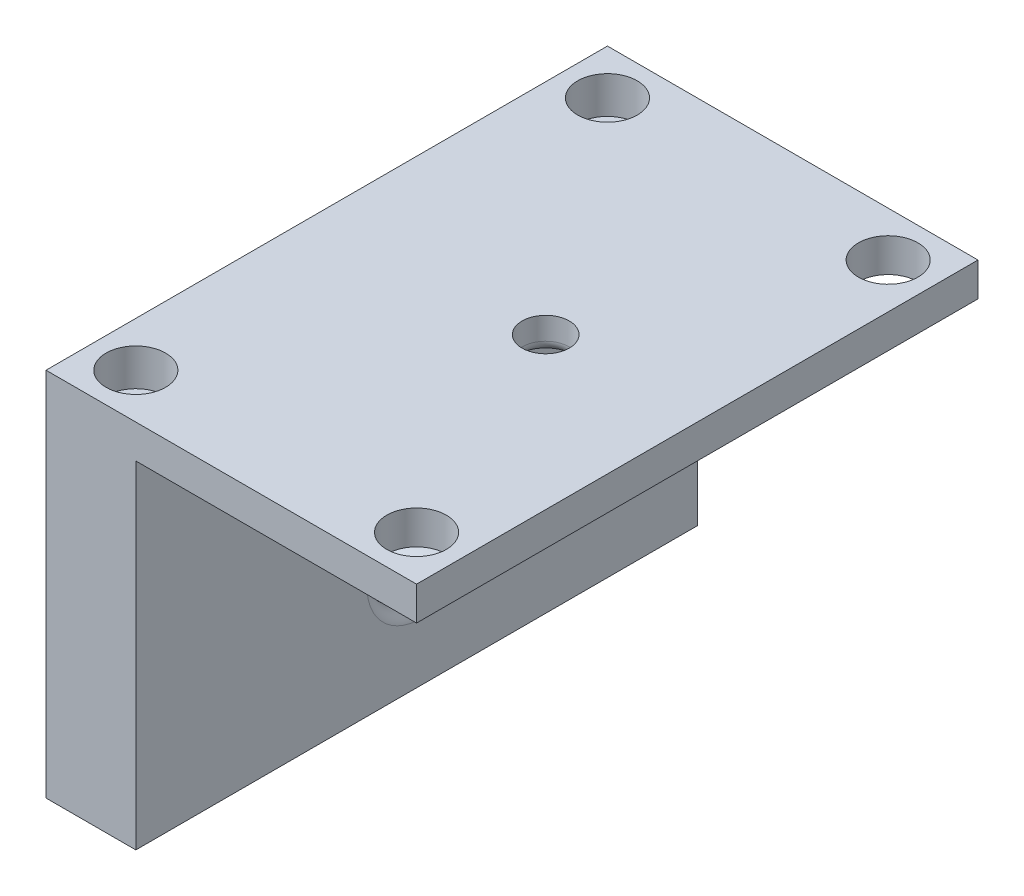
SolidWorks part; units mm, degrees
ref_plane "Front Plane" through (0, 0, 0) normal (0, 0, 1) x (1, 0, 0)
ref_plane "Top Plane" through (0, 0, 0) normal (0, 1, 0) x (1, 0, 0)
ref_plane "Right Plane" through (0, 0, 0) normal (1, 0, 0) x (0, 0, -1)
sketch "Sketch1" plane through (0, 0, 0) normal (0, 1, 0) x (1, 0, 0)
  line L1 (-10.223, 36.3848) -> (14.777, 36.3848)
  line L2 (-10.223, 36.3848) -> (-10.223, -13.6152)
  line L3 (-10.223, -13.6152) -> (14.777, -13.6152)
  line L4 (14.777, 36.3848) -> (14.777, -13.6152)
  circle A0 centre (1.277, 11.3848) radius 2.1
  dimension "D3" = 4.2
  dimension "D1" = 50
  dimension "D2" = 25
  dimension "D4" = 13.5
  dimension "D5" = 25
extrude "Boss-Extrude1" add sketch "Sketch1" along normal blind 3
sketch "Sketch2" plane through (-10.223, 0, 0) normal (-1, 0, 0) x (0, 0, 1)
  line L0 (13.75, 0) -> (-13.75, 0) construction
  line L1 (-36.3848, 3) -> (13.6152, 3)
  line L2 (-36.3848, 3) -> (-36.3848, 0)
  line L3 (-36.3848, 0) -> (13.6152, 0)
  line L4 (13.6152, 3) -> (13.6152, 0)
  line L5 (13.6152, 3) -> (13.6152, 0) construction
extrude "Boss-Extrude2" add sketch "Sketch2" along normal blind 8
sketch "Sketch3" plane through (0, 0, 0) normal (0, -1, 0) x (1, 0, 0)
  line L0 (-18.223, 13.6152) -> (14.777, 13.6152) construction
  line L1 (-18.223, -36.3848) -> (-10.223, -36.3848)
  line L2 (-18.223, -36.3848) -> (-18.223, 13.6152)
  line L3 (-18.223, 13.6152) -> (-10.223, 13.6152)
  line L4 (-10.223, -36.3848) -> (-10.223, 13.6152)
  dimension "D1" = 8
extrude "Boss-Extrude3" add sketch "Sketch3" along normal blind 30
sketch "Sketch4" plane through (0, 3, 0) normal (0, 1, 0) x (1, 0, 0)
  line L0 (-18.223, -13.6152) -> (-18.223, 36.3848) construction
  line L1 (14.777, 36.3848) -> (-18.223, 36.3848) construction
  line L2 (-18.223, -13.6152) -> (14.777, -13.6152) construction
  circle A0 centre (-14.223, 32.3848) radius 2.65
  circle A1 centre (-14.223, -9.6152) radius 2.65
  dimension "D2" = 5.3
  dimension "D4" = 5.3
  dimension "D5" = 4
  dimension "D6" = 4
  dimension "D1" = 4
  dimension "D3" = 4
extrude "Cut-Extrude1" cut sketch "Sketch4" against normal blind 3.3
ref_plane "Plane1" through (0, -13.5, 0) normal (0, 1, 0) x (1, 0, 0)
mirror "Mirror1" about plane through (0, -13.5, 0) normal (0, 1, 0) of "Cut-Extrude1"
fillet "Fillet1" radius 1 1 edges at (1.277, 0, -9.2848)
sketch "Sketch5" plane through (-18.223, 0, 0) normal (-1, 0, 0) x (0, 0, 1)
  line L0 (18.15, 0) -> (-18.15, 0) construction
  line L1 (-8.6015, -22.1212) -> (-8.3819, -18.2592) construction
  line L2 (-8.3819, -18.2592) -> (-11.6167, -16.138) construction
  line L3 (-11.6167, -16.138) -> (-15.0711, -17.8788) construction
  line L4 (-15.0711, -17.8788) -> (-15.2907, -21.7408) construction
  line L5 (-15.2907, -21.7408) -> (-12.0559, -23.862) construction
  line L6 (-12.0559, -23.862) -> (-8.6015, -22.1212) construction
  circle A0 centre (-11.8363, -20) radius 3.35 construction
  circle A1 centre (-11.8363, -20) radius 3.8682
  dimension "D1" = 20
  dimension "D2" = 6.7
extrude "Cut-Extrude2" cut sketch "Sketch5" against normal blind 9
fillet "Fillet2" radius 1 1 edges at (-10.223, -20, -7.968)
ref_plane "Plane2" through (-1.723, 0, 0) normal (-1, 0, 0) x (0, 0, 1)
mirror "Mirror2" about plane through (-1.723, 0, 0) normal (-1, 0, 0) of "Cut-Extrude1"
